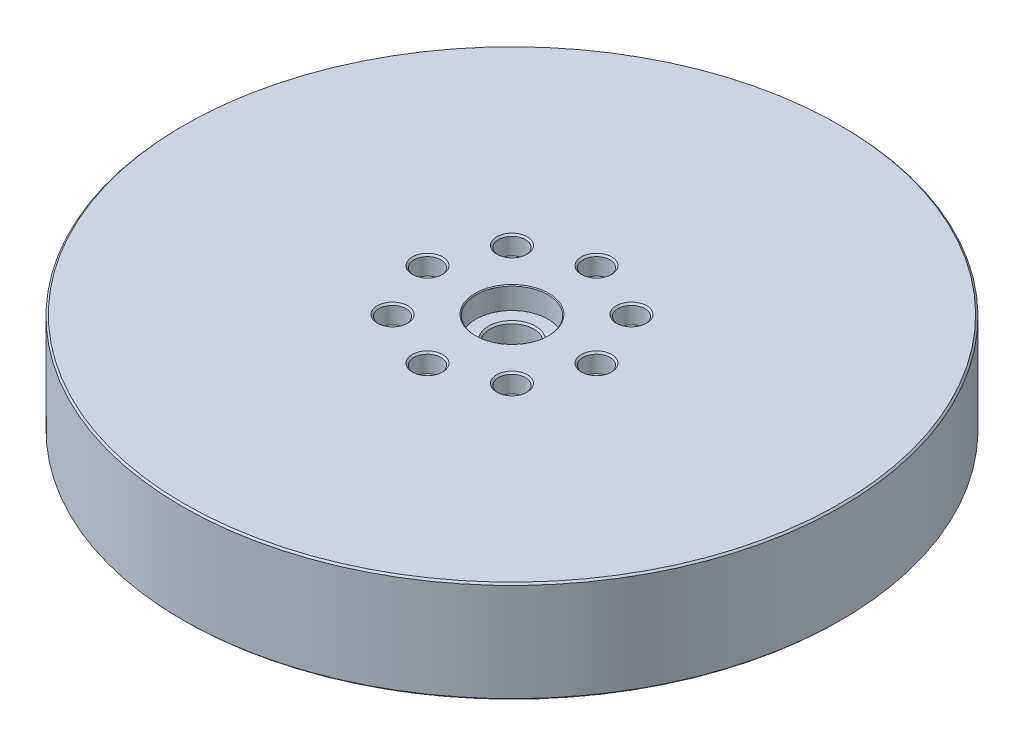
SolidWorks part; units mm, degrees
material "Ст 3 ГОСТ 380-88"
ref_plane "Front Plane" through (0, 0, 0) normal (0, 0, 1) x (1, 0, 0)
ref_plane "Top Plane" through (0, 0, 0) normal (0, 1, 0) x (1, 0, 0)
ref_plane "Right Plane" through (0, 0, 0) normal (1, 0, 0) x (0, 0, -1)
sketch "Sketch1" plane through (0, 0, 0) normal (1, 0, 0) x (0, 0, -1)
  line L0 (0, -14) -> (0, -31.7786) construction
  line L1 (-195, 60) -> (-195, 0)
  line L2 (-195, 0) -> (-185.5, 0)
  line L3 (-74.5, 0) -> (-74.5, -14)
  line L4 (-74.5, -14) -> (-15.5, -14)
  line L5 (-195, 60) -> (-185.5, 60)
  line L6 (0, 30.6711) -> (0, 60) construction
  line L7 (-13, 47) -> (-13, -11.5)
  line L8 (-13, -14) -> (0, -14) construction
  line L9 (0, 30.6711) -> (0, -14) construction
  line L10 (0, -14) -> (0, 30.6711) construction
  line L11 (-13, 60) -> (0, 60) construction
  line L12 (-15.5, 60) -> (-13, 57.5) construction
  line L13 (-15.5, -14) -> (-13, -11.5)
  line L14 (-21.25, 59.5) -> (-21.25, 47)
  line L15 (-21.25, 47) -> (-13, 47)
  line L16 (-21.25, 60) -> (-15.5, 60) construction
  line L17 (-13, 57.5) -> (-13, 47) construction
  line L18 (-21.75, 60) -> (-21.25, 59.5)
  line L19 (-185.5, 0) -> (-185.5, 10)
  line L20 (-185.5, 10) -> (-74.5, 10)
  line L21 (-74.5, 0) -> (-74.5, 10)
  line L22 (-185.5, 0) -> (-74.5, 0) construction
  line L23 (-185.5, 60) -> (-185.5, 50) construction
  line L24 (-185.5, 50) -> (-74.5, 50) construction
  line L25 (-74.5, 50) -> (-74.5, 60) construction
  line L26 (-185.5, 60) -> (-74.5, 60) construction
  line L27 (-74.5, 60) -> (-21.75, 60)
  line L28 (-185.5, 60) -> (-74.5, 60)
  dimension "D1" = 60
  dimension "D2" = 390
  dimension "D3" = 149
  dimension "D4" = 14
  dimension "D5" = 13
  dimension "D6" = 13
  dimension "D7" = 42.5
  dimension "D10" = 10
  dimension "D11" = 9.5
  dimension "D13" = 10
revolve "Revolve1" add sketch "Sketch1" angle 360 about L0
sketch "Sketch2" plane through (0, 60, 0) normal (0, 1, 0) x (1, 0, 0)
  line L0 (-50, 0) -> (0, 0) construction
  circle A0 centre (-50, 0) radius 4
  circle A1 centre (-35.3553, 35.3553) radius 4
  circle A2 centre (0, 50) radius 4
  circle A3 centre (35.3553, 35.3553) radius 4
  circle A4 centre (50, 0) radius 4
  circle A5 centre (35.3553, -35.3553) radius 4
  circle A6 centre (0, -50) radius 4
  circle A7 centre (-35.3553, -35.3553) radius 4
  point P21 (0, 0)
  dimension "D1" = 8
  dimension "D2" = 8
  dimension "D3" = 50
extrude "Cut-Extrude1" cut sketch "Sketch2" against normal through all both and the other way through all
sketch "Sketch3" plane through (0, 10, 0) normal (0, -1, 0) x (1, 0, 0)
  line L0 (0, 129.2853) -> (0, -136.9499) construction
  line L1 (0, 0) -> (0, 132.1781) construction
  line L2 (0, 0) -> (-104.479, 104.479) construction
  circle A0 centre (0, 82) radius 2
  circle A1 centre (0, 120) radius 2
  circle A2 centre (84.8528, 84.8528) radius 2
  circle A3 centre (57.9828, 57.9828) radius 2 construction
  circle A4 centre (120, 0) radius 2
  circle A5 centre (82, 0) radius 2
  circle A6 centre (84.8528, -84.8528) radius 2
  circle A7 centre (57.9828, -57.9828) radius 2 construction
  circle A8 centre (0, -120) radius 2
  circle A9 centre (0, -82) radius 2
  circle A10 centre (-84.8528, -84.8528) radius 2
  circle A11 centre (-57.9828, -57.9828) radius 2 construction
  circle A12 centre (-120, 0) radius 2
  circle A13 centre (-82, 0) radius 2
  circle A14 centre (-84.8528, 84.8528) radius 2
  circle A15 centre (-57.9828, 57.9828) radius 2 construction
  circle A16 centre (0, 0) radius 120 construction
  point P104 (0, 0)
  dimension "D1" = 4
  dimension "D4" = 120
  dimension "D3" = 240
  dimension "D2" = 82
  dimension "D6" = 45
  dimension "D5" = 8
extrude "Cut-Extrude2" [suppressed] cut sketch "Sketch3" against normal blind 15
ref_plane "Plane1" through (0, 30, 0) normal (0, -1, 0) x (-1, 0, 0)
mirror "Mirror1" [suppressed] about plane through (0, 30, 0) normal (0, -1, 0)
sketch "Sketch4" plane through (0, 60, 0) normal (0, 1, 0) x (1, 0, 0)
  circle A0 centre (0, 50) radius 8
  circle A1 centre (0, 0) radius 50 construction
  circle A2 centre (35.3553, 35.3553) radius 8
  circle A3 centre (50, 0) radius 8
  circle A4 centre (35.3553, -35.3553) radius 8
  circle A5 centre (0, -50) radius 8
  circle A6 centre (-35.3553, -35.3553) radius 8
  circle A7 centre (-50, 0) radius 8
  circle A8 centre (-35.3553, 35.3553) radius 8
  point P22 (0, 0)
  dimension "D1" = 16
  dimension "D2" = 8
extrude "Cut-Extrude3" cut sketch "Sketch4" against normal blind 12
sketch "Sketch5" plane through (0, -14, 0) normal (0, -1, 0) x (1, 0, 0)
  circle A0 centre (35.3553, -35.3553) radius 4 construction
  circle A1 centre (0, 0) radius 74.5
  circle A2 centre (0, 0) radius 74.5
  circle A3 centre (0, -50) radius 4 construction
  circle A4 centre (-35.3553, -35.3553) radius 4 construction
  circle A5 centre (-50, 0) radius 4 construction
  circle A6 centre (50, 0) radius 4 construction
  circle A7 centre (35.3553, 35.3553) radius 4 construction
  circle A8 centre (-35.3553, 35.3553) radius 4 construction
  circle A9 centre (0, 50) radius 4 construction
  circle A10 centre (35.3553, -35.3553) radius 4
  circle A11 centre (0, -50) radius 4
  circle A12 centre (-35.3553, -35.3553) radius 4
  circle A13 centre (-50, 0) radius 4
  circle A14 centre (50, 0) radius 4
  circle A15 centre (35.3553, 35.3553) radius 4
  circle A16 centre (-35.3553, 35.3553) radius 4
  circle A17 centre (0, 50) radius 4
  circle A18 centre (0, 0) radius 13 construction
  circle A19 centre (0, 0) radius 13
  dimension "D1" = 0
extrude "Boss-Extrude1" add sketch "Sketch5" along normal blind 1 from offset 30 separate body
sketch "Sketch6" plane through (0, -14, 0) normal (0, -1, 0) x (1, 0, 0)
  circle A1 centre (0, 0) radius 74.5
  circle A2 centre (0, 0) radius 74.5
  dimension "D1" = 0
extrude "Cut-Extrude4" cut sketch "Sketch6" against normal blind 2.5
sketch "Sketch7" plane through (0, 10, 0) normal (0, -1, 0) x (1, 0, 0)
  line L0 (0, 234.4435) -> (0, -294.1465) construction
  line L1 (0, 0) -> (28.7013, 69.291) construction
  line L3 (-28.7013, 69.291) -> (-70.4138, 169.9938) construction
  line L4 (28.2387, 69.4808) -> (69.9516, 170.1845)
  line L5 (-28.2387, 69.4808) -> (-69.9516, 170.1845)
  line L6 (28.7013, 69.291) -> (70.4138, 169.9938) construction
  line L7 (70.9878, 171.3797) -> (89.9519, 217.1632) construction
  line L8 (70.4138, 169.9938) -> (70.9878, 171.3797) construction
  line L9 (0, 75) -> (22.6048, 75) construction
  line L10 (0, 129.5) -> (22.6048, 129.5) construction
  line L11 (0, 184) -> (132.4756, 184) construction
  circle A1 centre (0, 0) radius 13 construction
  arc A2 (69.9516, 170.1845) -> (-69.9516, 170.1845) centre (0, 0) ccw
  circle A3 centre (0, 157) radius 2.6
  circle A4 centre (0, 0) radius 185.5 construction
  circle A6 centre (0, 102) radius 2.6
  arc A8 (-69.9516, 170.1845) -> (-70.4138, 169.9938) centre (0, 0) ccw construction
  arc A9 (28.2387, 69.4808) -> (-28.2387, 69.4808) centre (0, 0) ccw
  dimension "D1" = 22.5
  dimension "D2" = 184
  dimension "D3" = 371
  dimension "D5" = 0.5
  dimension "D6" = 75
  dimension "D7" = 5.2
  dimension "D4" = 109
  dimension "D8" = 54.5
  dimension "D9" = 55
extrude "Boss-Extrude3" add sketch "Sketch7" along normal blind 5 from offset 0.01 separate body
sketch "Sketch8" plane through (0, 4.99, 0) normal (0, -1, 0) x (1, 0, 0)
  line L2 (28.2387, 69.4808) -> (69.9516, 170.1845)
  line L3 (-69.9516, 170.1845) -> (-28.2387, 69.4808)
  line L4 (28.2387, 69.4808) -> (69.9516, 170.1845)
  line L5 (-69.9516, 170.1845) -> (-28.2387, 69.4808)
  circle A0 centre (0, 102) radius 2.6 construction
  circle A1 centre (0, 157) radius 2.6 construction
  arc A2 (28.2387, 69.4808) -> (-28.2387, 69.4808) centre (0, 0) ccw
  arc A3 (69.9516, 170.1845) -> (-69.9516, 170.1845) centre (0, 0) ccw
  arc A4 (28.2387, 69.4808) -> (-28.2387, 69.4808) centre (0, 0) ccw
  arc A5 (69.9516, 170.1845) -> (-69.9516, 170.1845) centre (0, 0) ccw
  circle A6 centre (0, 102) radius 2.6
  circle A7 centre (0, 157) radius 2.6
  dimension "D1" = 0
extrude "Boss-Extrude4" add sketch "Sketch8" along normal blind 5 separate body
chamfer "Chamfer3" distance 3.5 angle 45 2 edges at (0, -0.01, 99.4) (0, -0.01, 154.4)
chamfer "Chamfer4" distance 3.5 angle 45 2 edges at (0, 9.99, 104.6) (0, 9.99, 154.4)
sketch "Sketch9" plane through (0, 10, 0) normal (0, -1, 0) x (1, 0, 0)
  line L0 (0, 0) -> (0, 213.1478) construction
  circle A0 centre (0, 157) radius 2.6
  circle A1 centre (0, 157) radius 2.6 construction
  circle A3 centre (0, 102) radius 2.6
  circle A4 centre (0, 102) radius 2.6 construction
  circle A5 centre (111.0158, 111.0158) radius 2.6
  circle A6 centre (72.1249, 72.1249) radius 2.6
  circle A7 centre (157, 0) radius 2.6
  circle A8 centre (102, 0) radius 2.6
  circle A9 centre (111.0158, -111.0158) radius 2.6
  circle A10 centre (72.1249, -72.1249) radius 2.6
  circle A11 centre (0, -157) radius 2.6
  circle A12 centre (0, -102) radius 2.6
  circle A13 centre (-111.0158, -111.0158) radius 2.6
  circle A14 centre (-72.1249, -72.1249) radius 2.6
  circle A15 centre (-157, 0) radius 2.6
  circle A16 centre (-102, 0) radius 2.6
  circle A17 centre (-111.0158, 111.0158) radius 2.6
  circle A18 centre (-72.1249, 72.1249) radius 2.6
  point P42 (0, 0)
  dimension "D1" = 5.2
  dimension "D2" = 8
extrude "Cut-Extrude5" cut sketch "Sketch9" against normal blind 15
sketch "Sketch10" plane through (0, -11.5, 0) normal (0, -1, 0) x (1, 0, 0)
  circle A0 centre (0, 0) radius 65
  circle A1 centre (0, 0) radius 35
  dimension "D1" = 130
  dimension "D2" = 70
extrude "Cut-Extrude6" cut sketch "Sketch10" against normal blind 10
chamfer "Chamfer5" distance 1 angle 45 35 edges at (-35.3553, -1.5, 31.3553) (0, -1.5, 46) (35.3553, -1.5, 31.3553) (50, -1.5, -4) (35.3553, -1.5, -39.3553) (0, -1.5, -54) (-35.3553, -1.5, -39.3553) (-50, -1.5, -4) (0, -1.5, -65) (0, -1.5, -35) (0, -11.5, -35) (0, -11.5, -65) (0, 10, 185.5) (0, 10, 74.5) (0, 60, 195) (0, 0, 195) (-35.3553, 60, 43.3553) (-35.3553, 48, 43.3553) (-35.3553, 60, -27.3553) (-35.3553, 48, -27.3553) (-50, 60, 8) (-50, 48, 8) (0, 60, -42) (0, 48, -42) (35.3553, 60, -27.3553) (35.3553, 48, -27.3553) (50, 60, 8) (50, 48, 8) (35.3553, 60, 43.3553) (35.3553, 48, 43.3553) (0, 60, 58) (0, 48, 58) (0, -11.5, -13) (0, 47, 13) (0, -11.5, -74.5)
